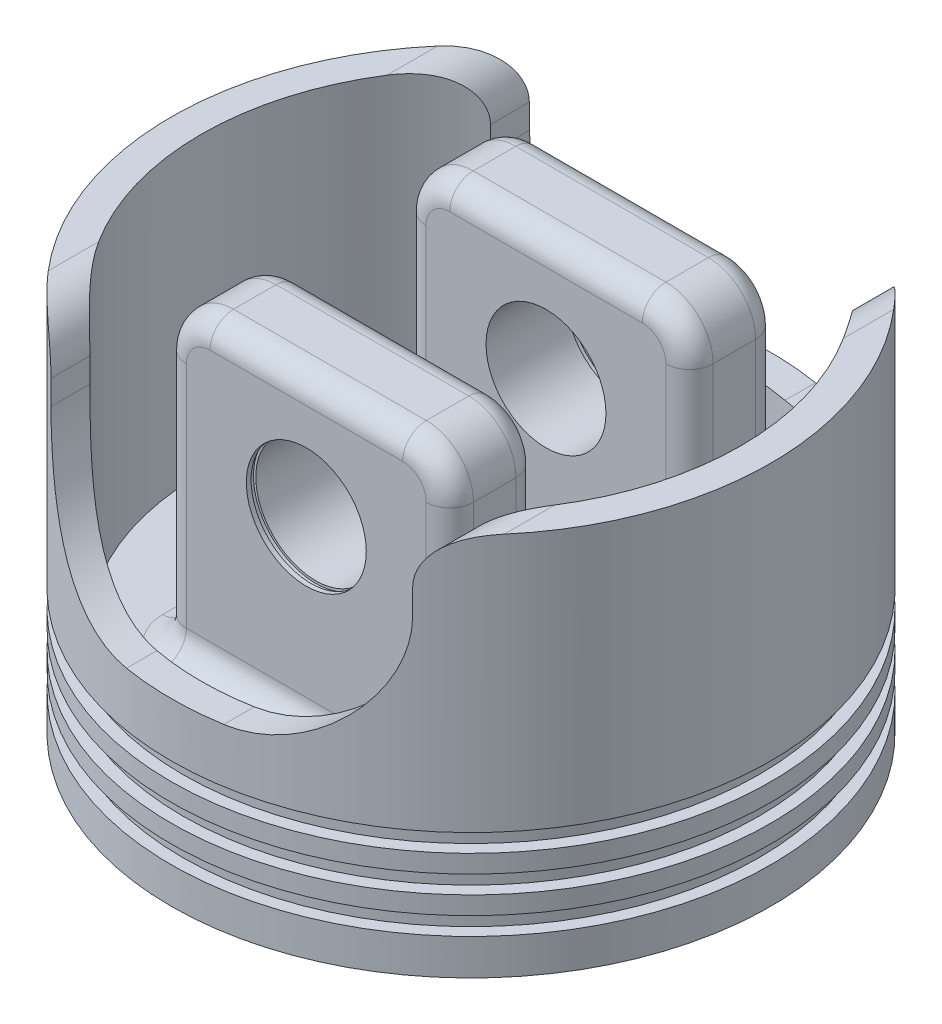
SolidWorks part; units mm, degrees
ref_plane "Płaszczyzna przednia" through (0, 0, 0) normal (0, 0, 1) x (1, 0, 0)
ref_plane "Płaszczyzna górna" through (0, 0, 0) normal (0, 1, 0) x (1, 0, 0)
ref_plane "Płaszczyzna prawa" through (0, 0, 0) normal (1, 0, 0) x (0, 0, -1)
sketch "Szkic1" plane through (0, 0, 0) normal (0, 1, 0) x (1, 0, 0)
  circle A0 centre (0, 0) radius 63.5
  dimension "D1" = 127
extrude "Dodanie-wyciągnięcie2" add sketch "Szkic1" along normal blind 81.28
sketch "Szkic2" plane through (0, 81.28, 0) normal (0, 1, 0) x (1, 0, 0)
  circle A0 centre (0, 0) radius 57.15
  dimension "r1" = 114.3
extrude "Wytnij-wyciągnięcie1" cut sketch "Szkic2" against normal blind 62.28
sketch "Szkic3" plane through (0, 0, 0) normal (0, 0, 1) x (1, 0, 0)
  line L0 (-63.5, 81.28) -> (-63.5, 87.0041)
  line L3 (38.3, 71.28) -> (38.3, 66.1)
  line L4 (10.3, 38.1) -> (-10.3, 38.1)
  line L5 (63.5, 81.28) -> (48.3, 81.28)
  line L6 (0, -44.704) -> (0, 44.704) construction
  line L7 (-38.3, 71.28) -> (-38.3, 66.1)
  line L8 (-63.5, 81.28) -> (-48.3, 81.28)
  line L9 (-63.5, 87.0041) -> (63.5, 87.0041)
  line L10 (63.5, 87.0041) -> (63.5, 81.28)
  arc A0 (38.3, 71.28) -> (48.3, 81.28) centre (48.3, 71.28) cw
  arc A1 (10.3, 38.1) -> (38.3, 66.1) centre (10.3, 66.1) ccw
  arc A2 (-38.3, 71.28) -> (-48.3, 81.28) centre (-48.3, 71.28) ccw
  arc A3 (-10.3, 38.1) -> (-38.3, 66.1) centre (-10.3, 66.1) cw
  point P15 (38.3, 38.1)
  point P25 (0, 38.1)
  dimension "D4" = 10
  dimension "D5" = 28
extrude "Wytnij-wyciągnięcie2" cut sketch "Szkic3" against normal mid plane 200
sketch "Szkic5" plane through (0, 0, 0) normal (0, -1, 0) x (-1, 0, 0)
  circle A0 centre (0, 0) radius 63.5
  circle A1 centre (0, 0) radius 60.96
  dimension "D1" = 121.92
extrude "Wytnij-wyciągnięcie3" cut sketch "Szkic5" against normal blind 3.81 from offset 7.62 offset against normal yes
sketch "Szkic6" plane through (0, 11.43, 0) normal (0, -1, 0) x (-1, 0, 0)
  circle A0 centre (0, 0) radius 63.5
  circle A1 centre (0, 0) radius 60.96
  dimension "D1" = 121.92
extrude "Wytnij-wyciągnięcie5" cut sketch "Szkic6" against normal blind 3.81 from offset 3.81 offset against normal yes
sketch "Szkic7" plane through (0, 15.24, 0) normal (0, 1, 0) x (1, 0, 0)
  circle A0 centre (0, 0) radius 63.5
  circle A1 centre (0, 0) radius 60.96
  dimension "D1" = 121.92
extrude "Wytnij-wyciągnięcie6" cut sketch "Szkic7" against normal blind 3.81 from offset 11.43
sketch "Szkic8" plane through (0, 19, 0) normal (0, 1, 0) x (1, 0, 0)
  line L1 (-30.4, 15.88) -> (30.4, 15.88)
  line L2 (-30.4, 15.88) -> (-30.4, 34.88)
  line L3 (-30.4, 34.88) -> (30.4, 34.88)
  line L4 (30.4, 15.88) -> (30.4, 34.88)
  line L5 (-30.4, 15.88) -> (30.4, 34.88) construction
  line L6 (-30.4, 34.88) -> (30.4, 15.88) construction
  line L7 (-30.4, -15.88) -> (30.4, -15.88)
  line L8 (-30.4, -15.88) -> (-30.4, -34.88)
  line L9 (-30.4, -34.88) -> (30.4, -34.88)
  line L10 (30.4, -15.88) -> (30.4, -34.88)
  line L11 (-30.4, -15.88) -> (30.4, -34.88) construction
  line L12 (-30.4, -34.88) -> (30.4, -15.88) construction
  point P0 (0, 25.38)
  point P5 (0, -25.38)
  dimension "D1" = 15.88
  dimension "D2" = 15.88
  dimension "D3" = 19
  dimension "D4" = 19
  dimension "D5" = 60.8
  dimension "D6" = 60.8
  dimension "D7" = 0
  dimension "D8" = 0
extrude "Dodanie-wyciągnięcie3" add sketch "Szkic8" along normal blind 63.5
sketch "Szkic9" plane through (0, 0, 34.88) normal (0, 0, 1) x (1, 0, 0)
  line L0 (-30.4, 82.5) -> (30.4, 82.5) construction
  circle A0 centre (0, 57.1) radius 12.7
  dimension "D2" = 25.4
  dimension "D1" = 25.4
extrude "Wytnij-wyciągnięcie7" cut sketch "Szkic9" against normal through all
fillet "Zaokrąglenie3" radius 10 4 edges at (-30.4, 82.5, -25.38) (30.4, 82.5, -25.38) (30.4, 82.5, 25.38) (-30.4, 82.5, 25.38)
fillet "Zaokrąglenie4" radius 5 20 edges at (30.4, 45.75, -34.88) (27.4711, 79.5711, -34.88) (-30.4, 45.75, -34.88) (-27.4711, 79.5711, -34.88) (-30.4, 45.75, -15.88) (-27.4711, 79.5711, -15.88) (30.4, 45.75, -15.88) (27.4711, 79.5711, -15.88) (-30.4, 45.75, 34.88) (-27.4711, 79.5711, 34.88) (30.4, 45.75, 34.88) (27.4711, 79.5711, 34.88) (30.4, 45.75, 15.88) (27.4711, 79.5711, 15.88) (-30.4, 45.75, 15.88) (-27.4711, 79.5711, 15.88) (0, 82.5, -34.88) (0, 82.5, -15.88) (0, 82.5, 34.88) (0, 82.5, 15.88)
fillet "Zaokrąglenie5" radius 5 16 edges at (28.9355, 19, -33.4155) (30.4, 19, -25.38) (28.9355, 19, -17.3445) (0, 19, -15.88) (-28.9355, 19, -17.3445) (-30.4, 19, -25.38) (-28.9355, 19, -33.4155) (-28.9355, 19, 33.4155) (-30.4, 19, 25.38) (-28.9355, 19, 17.3445) (0, 19, 15.88) (28.9355, 19, 17.3445) (30.4, 19, 25.38) (28.9355, 19, 33.4155) (0, 19, -34.88) (0, 19, 34.88)
sketch "Szkic10" plane through (0, 0, 34.88) normal (0, 0, 1) x (1, 0, 0)
  circle A0 centre (0, 57.1) radius 13.2
  circle A1 centre (0, 57.1) radius 12.7
  dimension "D1" = 26.4
extrude "Wytnij-wyciągnięcie8" cut sketch "Szkic10" against normal blind 1 from offset 1 offset against normal yes
mirror "Lustro1" about plane through (0, 0, 0) normal (0, 0, 1) of "Wytnij-wyciągnięcie8"
